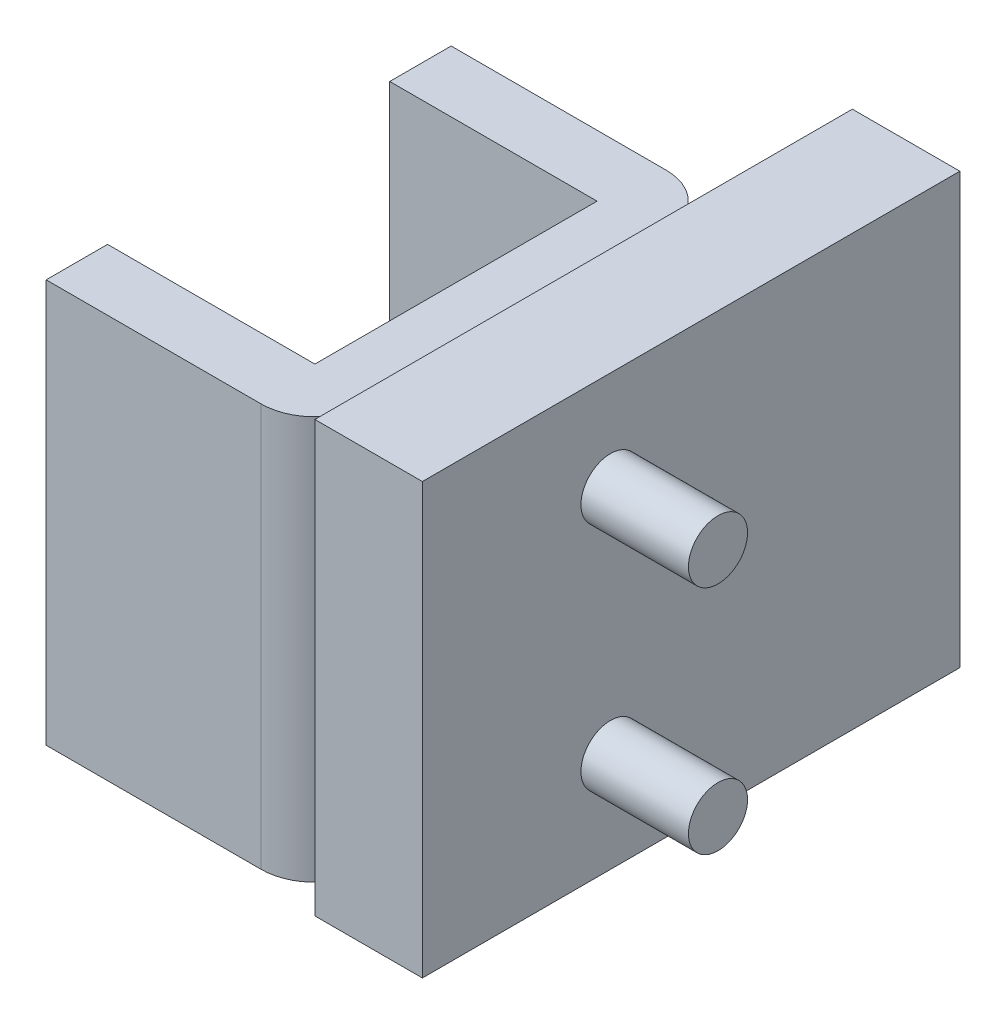
SolidWorks part; units mm, degrees
ref_plane "前视基准面" through (0, 0, 0) normal (0, 0, 1) x (1, 0, 0)
ref_plane "上视基准面" through (0, 0, 0) normal (0, 1, 0) x (1, 0, 0)
ref_plane "右视基准面" through (0, 0, 0) normal (1, 0, 0) x (0, 0, -1)
sketch "草图1" plane through (0, 0, 0) normal (0, 1, 0) x (1, 0, 0)
  line L0 (-35.9413, 35.7929) -> (-35.9413, 20.7229)
  line L1 (-35.9413, 20.7229) -> (-27.9413, 20.7229)
  line L2 (-35.9413, 35.7929) -> (-27.9413, 35.7929)
  line L3 (-25.9413, 33.7929) -> (-25.9413, 22.7229)
  arc A1 (-27.9413, 35.7929) -> (-25.9413, 33.7929) centre (-27.9413, 33.7929) cw
  arc A2 (-27.9413, 20.7229) -> (-25.9413, 22.7229) centre (-27.9413, 22.7229) ccw
  point P8 (-25.9413, 35.7929)
  point P11 (-25.9413, 20.7229)
  dimension "D1" = 10
  dimension "D3" = 2
  dimension "D4" = 2
  dimension "D2" = 15.07
sketch "草图5" plane through (0, 0, 0) normal (0, 1, 0) x (1, 0, 0)
extrude "凸台-拉伸4" add sketch "草图1" along normal blind 15
sketch "草图6" plane through (0, 15, 0) normal (0, 1, 0) x (1, 0, 0)
  line L0 (-33.6563, 33.5079) -> (-35.9413, 33.5079)
  line L1 (-35.9413, 35.7929) -> (-35.9413, 20.7229) construction
  line L2 (-35.9413, 33.5079) -> (-35.9413, 23.0079)
  line L3 (-35.9413, 23.0079) -> (-33.6563, 23.0079)
  line L4 (-33.6563, 33.5079) -> (-33.6563, 23.0079)
  line L8 (-28.2263, 33.5079) -> (-33.6563, 33.5079)
  line L9 (-33.6563, 33.5079) -> (-33.6563, 23.0079)
  line L10 (-33.6563, 23.0079) -> (-28.2263, 23.0079)
  line L11 (-28.2263, 23.0079) -> (-28.2263, 33.5079)
  line L12 (-28.2263, 33.5079) -> (-33.6563, 33.5079)
  line L13 (-33.6563, 33.5079) -> (-33.6563, 23.0079)
  line L14 (-33.6563, 23.0079) -> (-28.2263, 23.0079)
  line L15 (-28.2263, 23.0079) -> (-28.2263, 33.5079)
  dimension "D1" = 2.285
extrude "切除-拉伸2" cut sketch "草图6" against normal blind 15
sketch "草图7" plane through (0, 15, 0) normal (0, 1, 0) x (1, 0, 0)
  line L0 (-33.6563, 33.5079) -> (-35.9413, 33.5079)
  line L1 (-35.9413, 35.7929) -> (-35.9413, 20.7229) construction
  line L2 (-35.9413, 33.5079) -> (-35.9413, 23.0079)
  line L3 (-35.9413, 23.0079) -> (-33.6563, 23.0079)
  line L4 (-33.6563, 33.5079) -> (-33.6563, 23.0079) construction
  line L5 (-33.6563, 23.0079) -> (-33.6563, 33.5079)
extrude "切除-拉伸3" cut sketch "草图7" against normal blind 15
sketch "草图8" plane through (-25.9413, 0, 0) normal (1, 0, 0) x (0, 0, -1)
  line L1 (20.7229, -0.5) -> (40.7229, -0.5)
  line L2 (40.7229, -0.5) -> (40.7229, 15.5)
  line L3 (40.7229, 15.5) -> (20.7229, 15.5)
  line L4 (20.7229, 15.5) -> (20.7229, -0.5)
  line L7 (22.7229, 15) -> (33.7929, 15) construction
  line L9 (20.7229, 15) -> (20.7229, 0) construction
  dimension "D1" = 20
  dimension "D2" = 16
  dimension "D3" = 0.5
  dimension "D4" = 0
extrude "凸台-拉伸5" add sketch "草图8" along normal blind 4
sketch "草图9" plane through (-21.9413, 0, 0) normal (1, 0, 0) x (0, 0, -1)
  line L2 (20.7229, 15.5) -> (20.7229, -0.5) construction
  line L3 (20.7229, -0.5) -> (40.7229, -0.5) construction
  circle A0 centre (27.7229, 11.8) radius 1.1
  circle A1 centre (27.7229, 3.2) radius 1.1
  dimension "D1" = 8.6
  dimension "D2" = 2.2
  dimension "D3" = 2.2
  dimension "D4" = 3.7
  dimension "D5" = 7
  dimension "D6" = 7
extrude "凸台-拉伸6" add sketch "草图9" along normal blind 4
